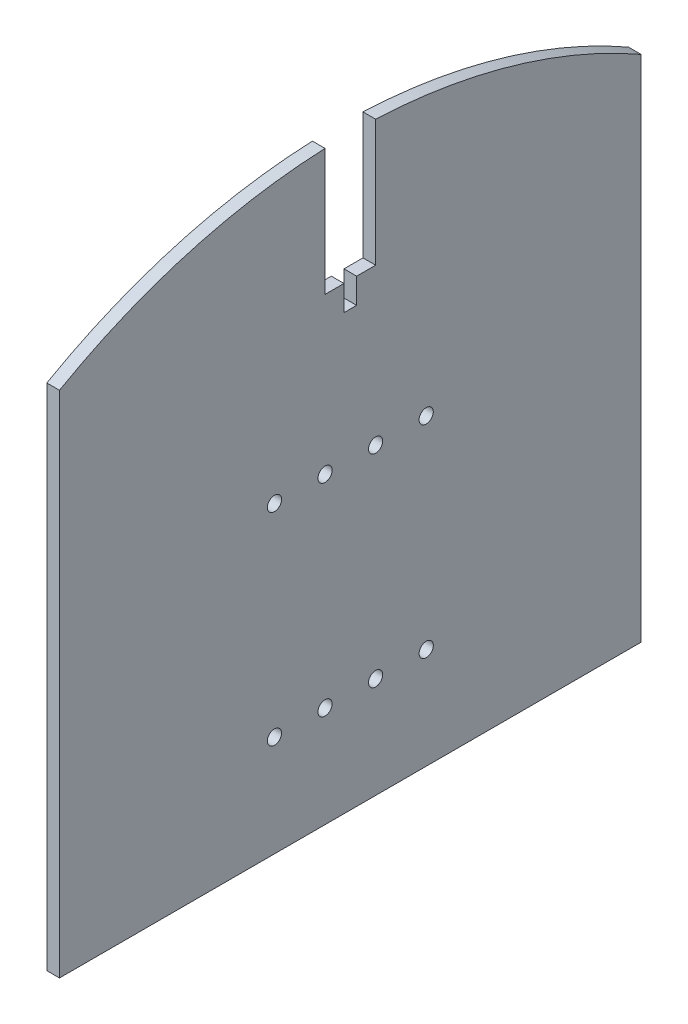
SolidWorks part; units mm, degrees
ref_plane "Front Plane" through (0, 0, 0) normal (0, 0, 1) x (1, 0, 0)
ref_plane "Top Plane" through (0, 0, 0) normal (0, 1, 0) x (1, 0, 0)
ref_plane "Right Plane" through (0, 0, 0) normal (1, 0, 0) x (0, 0, -1)
sketch "Sketch1" plane through (0, 0, 0) normal (1, 0, 0) x (0, 0, -1)
  line L0 (-294.386, 0) -> (0, 0) construction
  line L1 (0, 0) -> (146.05, 0)
  line L2 (0, 0) -> (0, 217.9119) construction
  line L3 (-12.7, 294.1119) -> (-12.7, 230.6119)
  line L4 (-12.7, 230.6119) -> (-3.175, 230.6119)
  line L5 (12.7, 230.6119) -> (12.7, 294.1119)
  line L6 (-146.05, 255.6023) -> (-146.05, 0)
  line L7 (146.05, 255.6023) -> (146.05, 0)
  line L8 (-146.05, 0) -> (0, 0)
  line L9 (-3.175, 230.6119) -> (-3.175, 217.9119)
  line L10 (-3.175, 217.9119) -> (3.175, 217.9119)
  line L11 (0, 0) -> (294.386, 0) construction
  line L12 (3.175, 217.9119) -> (3.175, 230.6119)
  line L13 (3.175, 230.6119) -> (12.7, 230.6119)
  line L14 (-3.175, 230.6119) -> (3.175, 230.6119) construction
  line L15 (0, 217.9119) -> (0, 230.6119) construction
  line L16 (-12.7, 230.6119) -> (12.7, 230.6119) construction
  arc A0 (294.386, 0) -> (12.7, 294.1119) centre (0, 0) ccw construction
  arc A1 (-146.05, 255.6023) -> (-12.7, 294.1119) centre (0, 0) cw
  arc A2 (-12.7, 294.1119) -> (-294.386, 0) centre (0, 0) ccw construction
  arc A3 (12.7, 294.1119) -> (146.05, 255.6023) centre (0, 0) cw
  point P12 (0, 217.9119)
  dimension "D1" = 588.772
  dimension "D3" = 25.4
  dimension "D2" = 292.1
  dimension "D4" = 63.5
  dimension "D5" = 6.35
  dimension "D6" = 12.7
extrude "Boss-Extrude1" add sketch "Sketch1" along normal blind 6.35
sketch "Sketch2" plane through (0, 0, 0) normal (1, 0, 0) x (0, 0, -1)
  line L0 (0, 50.8) -> (12.7, 50.8) construction
  line L1 (12.7, 50.8) -> (38.1, 50.8) construction
  line L2 (0, 0) -> (0, 189.439) construction
  circle A0 centre (12.7, 50.8) radius 3.5687
  circle A1 centre (38.1, 50.8) radius 3.5687
  circle A2 centre (12.7, 152.4) radius 3.5687
  circle A3 centre (38.1, 152.4) radius 3.5687
  circle A6 centre (-12.7, 50.8) radius 3.5687
  circle A7 centre (-38.1, 50.8) radius 3.5687
  circle A8 centre (-38.1, 152.4) radius 3.5687
  circle A9 centre (-12.7, 152.4) radius 3.5687
  dimension "D1" = 12.7
  dimension "E" = 7.1374
  dimension "D2" = 25.4
  dimension "D4" = 2
extrude "Cut-Extrude1" cut sketch "Sketch2" along normal blind 149.606
